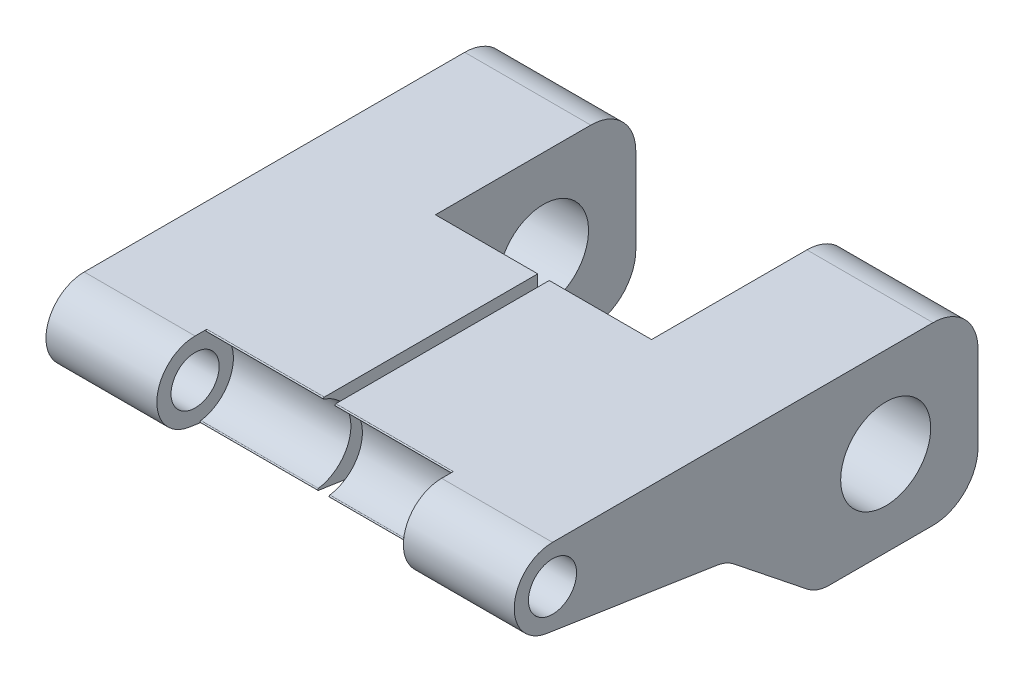
SolidWorks part; units mm, degrees
ref_plane "前视基准面" through (0, 0, 0) normal (0, 0, 1) x (1, 0, 0)
ref_plane "上视基准面" through (0, 0, 0) normal (0, 1, 0) x (1, 0, 0)
ref_plane "右视基准面" through (0, 0, 0) normal (1, 0, 0) x (0, 0, -1)
ref_plane "基准面4" through (57.25, 0, 0) normal (1, 0, 0) x (0, 0, -1)
sketch "草图1" plane through (57.25, 0, 0) normal (1, 0, 0) x (0, 0, -1)
  line L0 (-68.3224, -37.25) -> (-83, -37.25)
  line L1 (-61.875, -37.25) -> (-68.3224, -37.25)
  line L2 (-59.375, -39.75) -> (-59.375, -44.5)
  line L3 (-61.875, -47) -> (-67.6228, -47)
  line L5 (-83.3208, -41.4756) -> (-73.8675, -42.9194)
  line L6 (-72.9228, -43.3326) -> (-68.8695, -46.5639)
  circle A0 centre (-64.5, -42.25) radius 2.5 construction
  circle A1 centre (-64.5, -42.25) radius 2.5
  circle A2 centre (-83, -39.375) radius 1.3351
  circle A3 centre (-83, -39.375) radius 2.125
  arc A4 (-59.375, -44.5) -> (-61.875, -47) centre (-61.875, -44.5) cw
  arc A5 (-61.875, -37.25) -> (-59.375, -39.75) centre (-61.875, -39.75) cw
  arc A6 (-73.8675, -42.9194) -> (-72.9228, -43.3326) centre (-74.1695, -44.8965) cw
  arc A7 (-67.6228, -47) -> (-68.8695, -46.5639) centre (-67.6228, -45) cw
  point P22 (-73.34, -43)
  point P25 (-68.3224, -47)
  dimension "D7" = 2.5
  dimension "D8" = 2
  dimension "D9" = 2
  dimension "D1" = 5
  dimension "D2" = 5.125
  dimension "D3" = 4.75
  dimension "D4" = 18.5
  dimension "D5" = 2.875
  dimension "D6" = 4
extrude "凸台-拉伸1" add sketch "草图1" along normal blind 13 contours A7 L3 A4 L2 A5 L1 L0 A3 L5 A6 L6 A1 | A3 A2
sketch "草图2" plane through (0, 0, 0) normal (0, 1, 0) x (1, 0, 0)
  line L0 (70.25, -83) -> (57.25, -83) construction
  line L1 (63.25, -70.5) -> (56.6816, -70.5)
  line L2 (63.25, -70.5) -> (63.25, -57.7958)
  line L3 (63.25, -57.7958) -> (56.6816, -57.7958)
  line L4 (56.6816, -70.5) -> (56.6816, -57.7958)
  line L5 (57.5695, -70.2221) -> (56.6816, -70.2221)
  line L6 (57.5695, -70.2221) -> (57.5695, -85.5856)
  line L7 (57.5695, -85.5856) -> (56.6816, -85.5856)
  line L8 (56.6816, -70.2221) -> (56.6816, -85.5856)
  line L9 (64.0938, -83) -> (55.5971, -83)
  line L10 (64.0938, -83) -> (64.0938, -85.5856)
  line L11 (64.0938, -85.5856) -> (55.5971, -85.5856)
  line L12 (55.5971, -83) -> (55.5971, -85.5856)
  line L13 (70.25, -83) -> (57.25, -83)
  line L15 (63.25, -58.375) -> (63.25, -64.5) construction
  dimension "D1" = 70.5
  dimension "D3" = 6.5243
extrude "切除-拉伸2" cut sketch "草图2" against normal through all contours L5 L6 L1 L2 L3 L4 | L9 L6 L1 L8 | L11 L10 L9 L6 | L6 L9 L8 L7
sketch "草图3" plane through (64.0938, 0, 0) normal (-1, 0, 0) x (0, 0, 1)
  line L3 (83, -37.25) -> (83, -38.0399)
  line L4 (83, -40.7101) -> (83, -41.5246)
  line L5 (83, -41.5246) -> (83.3208, -41.4756)
  line L6 (83, -37.25) -> (83, -38.0399)
  line L7 (83, -40.7101) -> (83, -41.5246)
  line L8 (83, -41.5246) -> (83.3208, -41.4756)
  circle A0 centre (83, -39.375) radius 2.125
  arc A2 (83.3208, -41.4756) -> (83, -37.25) centre (83, -39.375) ccw
  arc A3 (83, -40.7101) -> (83, -38.0399) centre (83, -39.375) ccw
  arc A4 (83.3208, -41.4756) -> (83, -37.25) centre (83, -39.375) ccw
  arc A5 (83, -40.7101) -> (83, -38.0399) centre (83, -39.375) ccw
  arc M7 (83.3208, -41.4756) -> (83, -37.25) centre (83, -39.375) ccw
  line M8 (83, -37.25) -> (83, -38.0399)
  arc M9 (83, -38.0399) -> (83, -40.7101) centre (83, -39.375) cw
  line M10 (83, -40.7101) -> (83, -41.5246)
  dimension "D1" = 0
extrude "切除-拉伸3" cut sketch "草图3" along normal through all contours A0 M8 M10 M9 | A0 M10 M7 M8 M9
sketch "草图4" plane through (64.0938, 0, 0) normal (-1, 0, 0) x (0, 0, 1)
  line L0 (82.3481, -37.25) -> (82.981, -37.042)
  line L1 (82.981, -37.042) -> (83.2758, -37.268)
  line L2 (83.2758, -37.268) -> (82.9535, -37.5088)
  line L3 (82.9535, -37.5088) -> (82.3631, -37.3477)
  line L5 (83, -41.5246) -> (83, -41.5)
  line L6 (83, -37.25) -> (70.5, -37.25)
  line L7 (70.5, -37.25) -> (70.5, -45.2641)
  line L8 (70.5, -45.2641) -> (72.9228, -43.3326)
  line L9 (73.8675, -42.9194) -> (83, -41.5246)
  line L10 (83, -41.5246) -> (83, -41.5)
  line L11 (82.3481, -37.25) -> (70.5, -37.25)
  line L12 (70.5, -37.25) -> (70.5, -45.2641)
  line L13 (70.5, -45.2641) -> (72.9228, -43.3326)
  line L14 (73.8675, -42.9194) -> (83, -41.5246)
  arc A0 (82.3631, -37.3477) -> (82.3481, -37.25) centre (82.3481, -37.3) ccw
  circle A1 centre (82.6688, -41.5246) radius 0.05
  arc A2 (83, -37.25) -> (83, -41.5) centre (83, -39.375) ccw
  arc A3 (73.8675, -42.9194) -> (72.9228, -43.3326) centre (74.1695, -44.8965) ccw
  arc A4 (82.3631, -37.3477) -> (83, -41.5) centre (83, -39.375) ccw
  arc A5 (73.8675, -42.9194) -> (72.9228, -43.3326) centre (74.1695, -44.8965) ccw
  arc A6 (83.3208, -41.4756) -> (83, -37.25) centre (83, -39.375) ccw construction
  arc M13 (83.3208, -41.4756) -> (83, -37.25) centre (83, -39.375) ccw
  arc M14 (83, -37.25) -> (83, -41.5) centre (83, -39.375) ccw
  line M15 (83, -41.5) -> (83, -41.5246)
  dimension "D2" = 0.05
  dimension "D3" = 0.1
  dimension "D1" = 0
extrude "切除-拉伸4" cut sketch "草图4" along normal through all contours A0 L1 L0 M14 M13 | L3 L2 M13 M14 | A1 L14 M15 M14
fillet "圆角1" radius 1 1 edges at (60.4098, -45.2641, 70.5)
mirror "镜向2" about plane through (57.25, 0, 0) normal (1, 0, 0) of bodies 105
delete or keep bodies "实体-删除/保留 1" type delete bodies bodies 106
mirror "镜向3" about plane through (57.25, 0, 0) normal (1, 0, 0) of bodies 105
